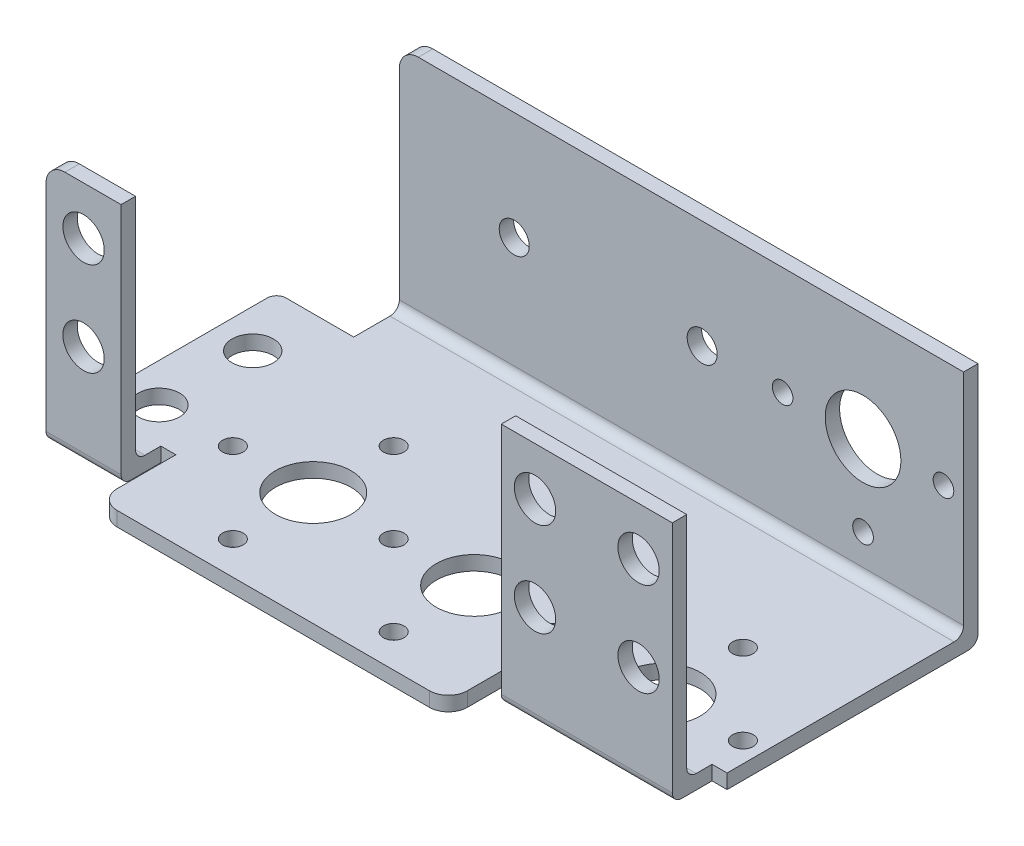
SolidWorks part; units mm, degrees
material "1060 Alloy"
ref_plane "Front" through (0, 0, 0) normal (0, 0, 1) x (1, 0, 0)
ref_plane "Top" through (0, 0, 0) normal (0, 1, 0) x (1, 0, 0)
ref_plane "Right" through (0, 0, 0) normal (1, 0, 0) x (0, 0, -1)
sketch "Sketch1" plane through (0, 0, 0) normal (0, 1, 0) x (1, 0, 0)
  line L0 (-57.15, 17.36) -> (57.15, 17.36)
  line L1 (57.15, 17.36) -> (57.15, -17.36)
  line L2 (-57.15, -17.36) -> (57.15, -17.36)
  line L3 (-57.15, -17.36) -> (-57.15, 17.36)
  line L4 (0, 17.36) -> (0, -17.36) construction
  point P6 (0, 0)
  dimension "D1" = 114.3
  dimension "D2" = 34.72
extrude "Boss-Extrude1" add sketch "Sketch1" along normal blind 1.524
ref_plane "Plane1" through (0, 1.524, 0) normal (0, 1, 0) x (1, 0, 0)
sketch "Sketch2" plane through (0, 1.524, 0) normal (0, 1, 0) x (1, 0, 0)
  line L0 (-49, 17.36) -> (-49, 11.01)
  line L1 (57.15, 17.36) -> (-57.15, 17.36) construction
  line L2 (-49, 11.01) -> (-57.15, 11.01)
  line L3 (-57.15, 17.36) -> (-57.15, -17.36) construction
  line L4 (-57.15, 11.01) -> (-57.15, 17.36)
  line L5 (-57.15, 17.36) -> (-49, 17.36)
  line L6 (-53.075, 11.01) -> (-53.075, -17.36) construction
  line L7 (-57.15, -17.36) -> (57.15, -17.36) construction
  line L8 (-57.15, -13.36) -> (-49.2125, -13.36)
  line L9 (-47.625, -13.36) -> (-47.625, -17.36)
  line L10 (-47.625, -17.36) -> (-57.15, -17.36)
  line L11 (-57.15, -13.36) -> (-57.15, -17.36)
  line L12 (-47.625, -13.36) -> (-47.625, -9.16)
  line L13 (-47.625, -9.16) -> (-49.2125, -9.16)
  line L14 (-49.2125, -9.16) -> (-49.2125, -13.36)
  line L15 (0, 17.36) -> (0, -17.36) construction
  line L16 (-10.625, -13.36) -> (-10.625, -9.16)
  line L17 (-10.625, -9.16) -> (-9.0375, -9.16)
  line L18 (-9.0375, -9.16) -> (-9.0375, -13.36)
  line L19 (-9.0375, -13.36) -> (0, -13.36)
  line L20 (-10.625, -13.36) -> (-10.625, -17.36)
  line L21 (-10.625, -17.36) -> (0, -17.36)
  line L23 (-47.625, -13.36) -> (-9.0375, -13.36) construction
  line L24 (0, -13.36) -> (0, -17.36)
  circle A0 centre (-53.075, 4.41) radius 2.184
  circle A1 centre (-53.075, -5.5) radius 2.184
  dimension "D3" = 4.368
  dimension "D1" = 8.15
  dimension "D2" = 6.35
  dimension "D4" = 9.91
  dimension "D5" = 6.6
  dimension "D6" = 4
  dimension "D7" = 9.525
  dimension "D8" = 1.5875
  dimension "D9" = 8.2
  dimension "D10" = 1.5875
  dimension "D11" = 37
  dimension "D12" = 4
extrude "Cut-Extrude1" cut sketch "Sketch2" against normal up to surface (1.524 mm away) up to face at (0, 0, 0)
mirror "Mirror1" about plane through (0, 0, 0) normal (1, 0, 0) of "Cut-Extrude1"
sketch "Sketch3" plane through (0, 1.524, 0) normal (0, 1, 0) x (1, 0, 0)
  line L0 (-47.625, -17.36) -> (-10.625, -17.36) construction
  line L1 (-57.15, 11.01) -> (-57.15, -13.36) construction
  circle A0 centre (-36.9062, -5.36) radius 4
  dimension "D1" = 8
  dimension "D3" = 20.2438
  dimension "D2" = 12
extrude "Cut-Extrude2" cut sketch "Sketch3" against normal mid plane 100
sketch "Sketch4" plane through (0, 1.524, 0) normal (0, 1, 0) x (1, 0, 0)
  line L0 (49, 17.36) -> (-49, 17.36) construction
  circle A0 centre (-36.9062, 3.14) radius 1.09
  circle A1 centre (-36.9062, -5.36) radius 4 construction
  dimension "D1" = 2.18
  dimension "D2" = 8.5
  dimension "D3" = 14.22
extrude "Cut-Extrude3" cut sketch "Sketch4" against normal mid plane 100
pattern_circular "CirPattern1" count 4 over 360 about axis through (-36.9062, 0, 5.36) along (0, 1, 0) of "Cut-Extrude3"
sketch "Sketch6" plane through (0, 1.524, 0) normal (0, 1, 0) x (1, 0, 0)
  line L0 (-28.4062, -4.27) -> (-28.4062, -17.36) construction
  line L1 (-47.625, -17.36) -> (-10.625, -17.36) construction
  line L3 (-57.15, 11.01) -> (-57.15, -13.36) construction
  circle A0 centre (-28.4062, -5.36) radius 1.09 construction
  dimension "D1" = 28.7438
ref_plane "Plane2" through (-28.4062, 0, 0) normal (-1, 0, 0) x (0, 0, 1)
mirror "Mirror2" about plane through (-28.4062, 0, 0) normal (-1, 0, 0) of "CirPattern1", "Cut-Extrude2", "Cut-Extrude3"
sketch "Sketch7" plane through (0, 1.524, 0) normal (0, 1, 0) x (1, 0, 0)
  line L0 (0, 17.36) -> (0, -13.36) construction
  line L1 (49, 17.36) -> (-49, 17.36) construction
  line L2 (9.0375, -13.36) -> (-9.0375, -13.36) construction
  line L3 (-23.9062, -5.36) -> (0, -5.36) construction
  circle A0 centre (-19.9062, -5.36) radius 4 construction
  circle A1 centre (0, -5.36) radius 4
  dimension "D1" = 5.36
extrude "Cut-Extrude4" cut sketch "Sketch7" against normal blind 100
sketch "Sketch8" plane through (0, 1.524, 0) normal (0, 1, 0) x (1, 0, 0)
  line L0 (0, -9.36) -> (0, 3.14) construction
  circle A0 centre (0, -5.36) radius 4 construction
  circle A1 centre (0, 3.14) radius 1.09
  dimension "D1" = 2.18
  dimension "D2" = 8.5
extrude "Cut-Extrude5" cut sketch "Sketch8" against normal blind 100
pattern_circular "CirPattern2" count 4 over 360 about axis through (0, 0, 5.36) along (0, 1, 0) skipping 2 of "Cut-Extrude5"
sketch "Sketch9" plane through (0, 1.524, 0) normal (0, 1, 0) x (1, 0, 0)
  line L0 (-57.15, -13.36) -> (-57.15, -11.836)
  line L1 (-57.15, 11.01) -> (-57.15, -13.36) construction
  line L2 (-57.15, -11.836) -> (-49.2125, -11.836)
  line L3 (-49.2125, -9.16) -> (-49.2125, -13.36) construction
  line L4 (-49.2125, -11.836) -> (-49.2125, -13.36)
  line L5 (-49.2125, -13.36) -> (-57.15, -13.36)
  dimension "D1" = 1.524
extrude "Boss-Extrude2" add sketch "Sketch9" along normal blind 24.2
mirror "Mirror4" about plane through (0, 0, 0) normal (1, 0, 0) of "Boss-Extrude2"
sketch "Sketch10" plane through (0, 1.524, 0) normal (0, 1, 0) x (1, 0, 0)
  line L0 (-49, 17.36) -> (49, 17.36)
  line L1 (49, 17.36) -> (49, 15.836)
  line L2 (49, 11.01) -> (49, 17.36) construction
  line L3 (49, 15.836) -> (-49, 15.836)
  line L4 (-49, 11.01) -> (-49, 17.36) construction
  line L5 (-49, 15.836) -> (-49, 17.36)
  line L6 (-9.0375, -13.36) -> (9.0375, -13.36)
  line L7 (-9.0375, -13.36) -> (-9.0375, -11.836)
  line L9 (-9.0375, -13.36) -> (-9.0375, -9.16) construction
  line L11 (-9.0375, -11.836) -> (9.0375, -11.836)
  line L12 (9.0375, -13.36) -> (9.0375, -9.16) construction
  line L13 (9.0375, -11.836) -> (9.0375, -13.36)
  dimension "D1" = 1.524
  dimension "D2" = 1.524
extrude "Boss-Extrude3" add sketch "Sketch10" along normal blind 24.2
ref_plane "Plane3" through (0, 0, 13.36) normal (0, 0, 1) x (1, 0, 0)
sketch "Sketch11" plane through (0, 0, 13.36) normal (0, 0, 1) x (1, 0, 0)
  line L0 (-53.1813, 25.724) -> (-53.1813, 0) construction
  line L1 (-57.15, 25.724) -> (-49.2125, 25.724) construction
  line L2 (-49.2125, 0) -> (-57.15, 0) construction
  circle A0 centre (-53.1813, 20.644) radius 2.1844
  circle A1 centre (-53.1813, 10.734) radius 2.1844
  dimension "D1" = 5.08
  dimension "D2" = 9.91
  dimension "D3" = 4.3688
extrude "Cut-Extrude6" cut sketch "Sketch11" against normal blind 24.2
mirror "Mirror5" about plane through (0, 0, 0) normal (1, 0, 0) of "Cut-Extrude6"
ref_plane "Plane4" through (0, 0, 13.36) normal (0, 0, 1) x (1, 0, 0)
sketch "Sketch12" plane through (0, 0, 13.36) normal (0, 0, 1) x (1, 0, 0)
  line L0 (0, 25.724) -> (0, 0) construction
  line L1 (-9.0375, 25.724) -> (9.0375, 25.724) construction
  circle A0 centre (-5.4713, 20.644) radius 2.1844
  circle A1 centre (-5.4713, 10.734) radius 2.1844
  circle A2 centre (-53.1812, 10.734) radius 2.1844 construction
  circle A3 centre (5.4713, 10.734) radius 2.1844
  circle A4 centre (5.4713, 20.644) radius 2.1844
  dimension "D1" = 4.3688
  dimension "D2" = 9.91
  dimension "D4" = 5.08
  dimension "D3" = 47.71
extrude "Cut-Extrude8" cut sketch "Sketch12" against normal blind 24.2
fillet "Fillet1" radius 1 10 edges at (53.1813, 0, 13.36) (-53.1813, 1.524, 11.836) (53.1813, 1.524, 11.836) (0, 1.524, -15.836) (0, 1.524, 11.836) (-57.15, 0.762, -11.01) (-53.1813, 0, 13.36) (0, 0, 13.36) (0, 0, -17.36) (57.15, 0.762, -11.01)
ref_plane "Plane5" through (0, 0, -15.836) normal (0, 0, 1) x (1, 0, 0)
sketch "Sketch13" plane through (0, 0, -15.836) normal (0, 0, 1) x (1, 0, 0)
  line L0 (10.625, 0) -> (47.625, 0) construction
  line L1 (0, 0) -> (0, 25.724) construction
  line L2 (-49, 25.724) -> (49, 25.724) construction
  line L4 (8.5, 2.524) -> (8.5, 25.724) construction
  line L5 (-49, 2.524) -> (49, 2.524) construction
  circle A0 centre (36.8628, 14.2875) radius 1.5875
  circle A1 centre (17, 14.2875) radius 1.5875
  dimension "D1" = 3.175
  dimension "D2" = 14.2875
  dimension "D3" = 8.5
  dimension "D4" = 19.8628
  dimension "D5" = 8.5
extrude "Cut-Extrude9" cut sketch "Sketch13" against normal blind 24.2
mirror "Mirror6" about plane through (0, 0, 0) normal (1, 0, 0) of "Cut-Extrude9"
fillet "Fillet2" radius 2 8 edges at (10.625, 0.762, 17.36) (47.625, 0.762, 17.36) (-10.625, 0.762, 17.36) (-47.625, 0.762, 17.36) (-49, 25.724, -16.598) (49, 25.724, -16.598) (57.15, 25.724, 12.598) (-57.15, 25.724, 12.598)
sketch "Sketch14" plane through (0, 0, -15.836) normal (0, 0, 1) x (1, 0, 0)
  line L0 (0, 25.724) -> (0, 0) construction
  line L1 (-47, 25.724) -> (47, 25.724) construction
  line L2 (38.4503, 14.2875) -> (0, 14.2875) construction
  circle A0 centre (36.8628, 14.2875) radius 1.5875 construction
  circle A1 centre (0, 14.2875) radius 4
  dimension "D1" = 8
  dimension "D2" = 14.2875
extrude "Cut-Extrude10" cut sketch "Sketch14" against normal blind 24.2
sketch "Sketch15" plane through (0, 0, -15.836) normal (0, 0, 1) x (1, 0, 0)
  circle A0 centre (0, 5.7875) radius 1.09
  circle A1 centre (0, 14.2875) radius 4 construction
  dimension "D1" = 2.18
  dimension "D2" = 8.5
  dimension "D3" = 5.7875
extrude "Cut-Extrude11" cut sketch "Sketch15" against normal blind 24.2
pattern_circular "CirPattern3" count 4 over 360 about axis through (0, 14.2875, 0) along (0, 0, 1) skipping 2 of "Cut-Extrude11"
sketch "Sketch18" plane through (0, 1.524, 0) normal (0, 1, 0) x (1, 0, 0)
  line L1 (10.625, -9.16) -> (58.8597, -9.16)
  line L2 (10.625, -9.16) -> (10.625, 20.9227)
  line L3 (10.625, 20.9227) -> (58.8597, 20.9227)
  line L4 (58.8597, -9.16) -> (58.8597, 20.9227)
  line L5 (58.8597, -9.16) -> (10.625, -9.16)
  line L6 (58.8597, -9.16) -> (58.8597, -20.3024)
  line L7 (58.8597, -20.3024) -> (10.625, -20.3024)
  line L8 (10.625, -9.16) -> (10.625, -20.3024)
extrude "Cut-Extrude13" cut sketch "Sketch18" against normal blind 19 and the other way blind 30 contours L1 L8 L7 L6 | L1 L4 L3 L2
